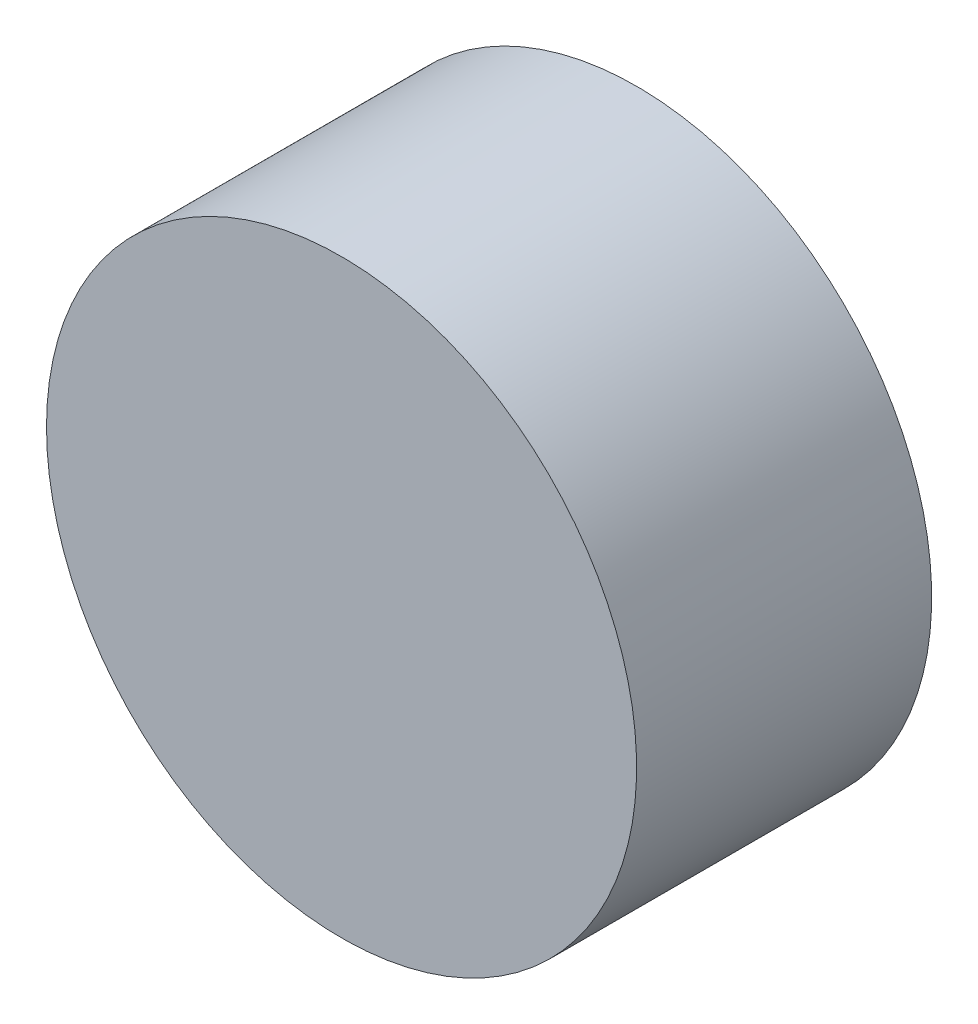
SolidWorks part; units mm, degrees
ref_plane "Front Plane" through (0, 0, 0) normal (0, 0, 1) x (1, 0, 0)
ref_plane "Top Plane" through (0, 0, 0) normal (0, 1, 0) x (1, 0, 0)
ref_plane "Right Plane" through (0, 0, 0) normal (1, 0, 0) x (0, 0, -1)
ref_plane "Plane1" through (0, 0, 0) normal (0, -1, 0) x (1, 0, 0)
sketch "Sketch1" plane through (0, 0, 0) normal (0, -1, 0) x (1, 0, 0)
  line L0 (10, 10) -> (0, 10)
  line L1 (0, 10) -> (0, 0)
  line L2 (0, 0) -> (10, 0)
  line L3 (10, 0) -> (10, 10)
  line L4 (0, 10) -> (0, 0) construction
revolve "Revolve1" add sketch "Sketch1" angle 360 about L4
